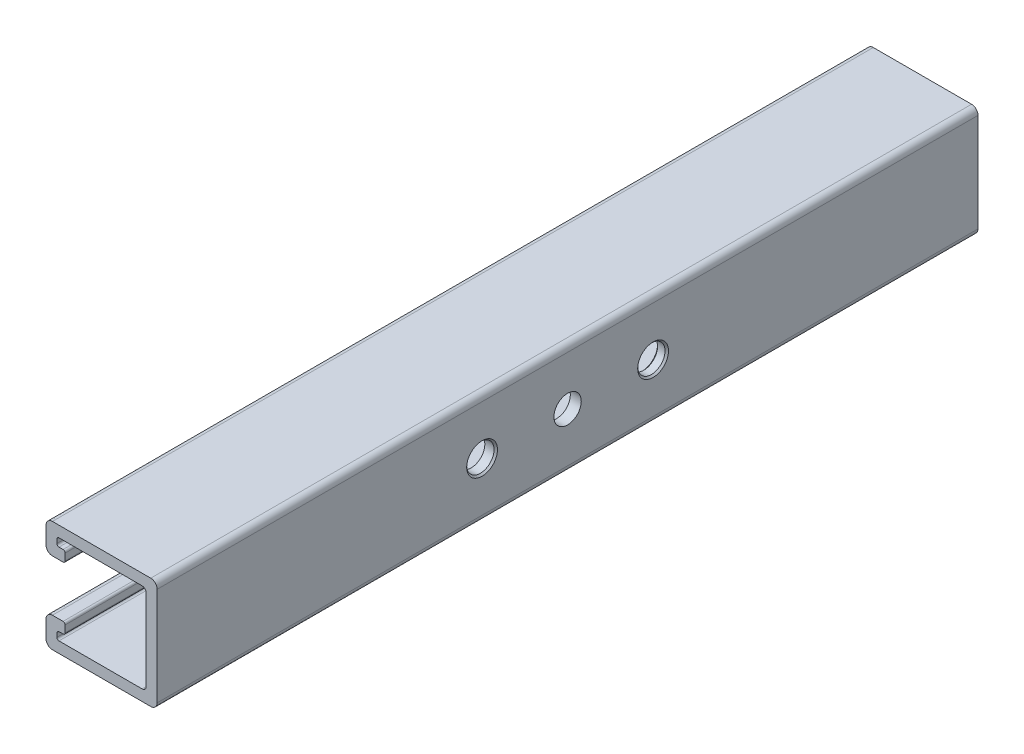
SolidWorks part; units mm, degrees
material "S-Glass Fiber"
ref_plane "Front Plane" through (0, 0, 0) normal (0, 0, 1) x (1, 0, 0)
ref_plane "Top Plane" through (0, 0, 0) normal (0, 1, 0) x (1, 0, 0)
ref_plane "Right Plane" through (0, 0, 0) normal (1, 0, 0) x (0, 0, -1)
sketch "Sketch1" plane through (0, 0, 0) normal (0, 0, 1) x (1, 0, 0)
  line L0 (-13.5255, 9.525) -> (-18.2499, 9.525)
  line L1 (-20.6375, 11.9126) -> (-20.6375, 18.2499)
  line L2 (-18.2499, 20.6375) -> (18.2499, 20.6375)
  line L3 (20.6375, 18.2499) -> (20.6375, -18.2499)
  line L4 (18.2499, -20.6375) -> (-18.2499, -20.6375)
  line L5 (-20.6375, -18.2499) -> (-20.6375, -11.9126)
  line L6 (-18.2499, -9.525) -> (-13.5255, -9.525)
  line L7 (0, 0) -> (20.6375, 0) construction
  line L8 (0, 0) -> (0, 20.6375) construction
  arc A0 (-20.6375, 18.2499) -> (-18.2499, 20.6375) centre (-18.2499, 18.2499) cw
  arc A1 (-18.2499, 9.525) -> (-20.6375, 11.9126) centre (-18.2499, 11.9126) cw
  arc A2 (-20.6375, -11.9126) -> (-18.2499, -9.525) centre (-18.2499, -11.9126) cw
  arc A3 (-18.2499, -20.6375) -> (-20.6375, -18.2499) centre (-18.2499, -18.2499) cw
  arc A4 (20.6375, -18.2499) -> (18.2499, -20.6375) centre (18.2499, -18.2499) cw
  arc A5 (18.2499, 20.6375) -> (20.6375, 18.2499) centre (18.2499, 18.2499) cw
  point P14 (-20.6375, 20.6375)
  point P23 (20.6375, -20.6375)
  point P26 (20.6375, 20.6375)
  dimension "D4" = 2.3876
  dimension "D1" = 41.275
  dimension "D2" = 41.275
  dimension "D3" = 19.05
  dimension "D5" = 7.112
extrude "Extrude-Thin1" add sketch "Sketch1" against normal blind 304.8 thin
fillet "Fillet2" radius 0.762 8 edges at (-16.5735, 13.589, -152.4) (-16.5735, -16.5735, -152.4) (-16.5735, 16.5735, -152.4) (-13.5255, 13.589, -152.4) (-13.5255, 9.525, -152.4) (-13.5255, -9.525, -152.4) (-13.5255, -13.589, -152.4) (-16.5735, -13.589, -152.4)
fillet "Fillet3" radius 1.524 2 edges at (16.5735, 16.5735, -152.4) (16.5735, -16.5735, -152.4)
sketch "Sketch3" plane through (0, 0, 0) normal (1, 0, 0) x (0, 0, -1)
  line L0 (0, 0) -> (304.8, 0) construction
  line L1 (304.8, 18.2499) -> (304.8, -18.2499) construction
  line L2 (0, 0) -> (0, 20.6375) construction
  line L3 (304.8, 0) -> (304.8, 20.6375) construction
  line L4 (304.8, 20.6375) -> (0, 20.6375) construction
  point P3 (101.6, 0)
  point P4 (203.2, 0)
  dimension "D1" = 101.6
  dimension "D2" = 101.6
sketch "Sketch4" plane through (20.6375, 0, 0) normal (1, 0, 0) x (0, 0, -1)
  line L0 (0, 0) -> (304.8, 0) construction
  line L1 (0, 18.2499) -> (0, -18.2499) construction
  line L2 (304.8, 18.2499) -> (304.8, -18.2499) construction
  line L3 (184.15, 5.08) -> (152.4, 5.08) construction
  line L4 (152.4, 5.08) -> (120.65, 5.08) construction
  circle A0 centre (152.4, 0) radius 5.08
  circle A1 centre (184.15, 0) radius 5.08
  circle A2 centre (120.65, 0) radius 5.08
  dimension "D1" = 10.16
  dimension "D2" = 10.16
  dimension "D3" = 31.75
extrude "Cut-Extrude1" cut sketch "Sketch4" against normal through all
chamfer "Chamfer1" distance 0.635 angle 45 3 edges at (20.6375, 0, -125.73) (16.5735, 0, -179.07) (20.6375, 0, -189.23)
sketch "Sketch5" [suppressed] plane through (20.6375, 0, 0) normal (1, 0, 0) x (0, 0, -1)
  line L1 (304.8, -20.6375) -> (0, -20.6375) construction
  line L2 (304.8, -20.6375) -> (304.8, 20.6375)
  line L3 (304.8, 20.6375) -> (0, 20.6375) construction
  line L4 (0, -20.6375) -> (0, 20.6375)
  line L5 (304.8, -20.6375) -> (0, 20.6375) construction
  line L6 (304.8, 20.6375) -> (0, -20.6375) construction
  circle A0 centre (184.15, 0) radius 5.08 construction
  circle A1 centre (152.4, 0) radius 5.08 construction
  circle A2 centre (120.65, 0) radius 5.08 construction
  circle A3 centre (184.15, 0) radius 5.08
  circle A4 centre (152.4, 0) radius 5.08
  circle A5 centre (120.65, 0) radius 5.08
  point P0 (152.4, 0)
